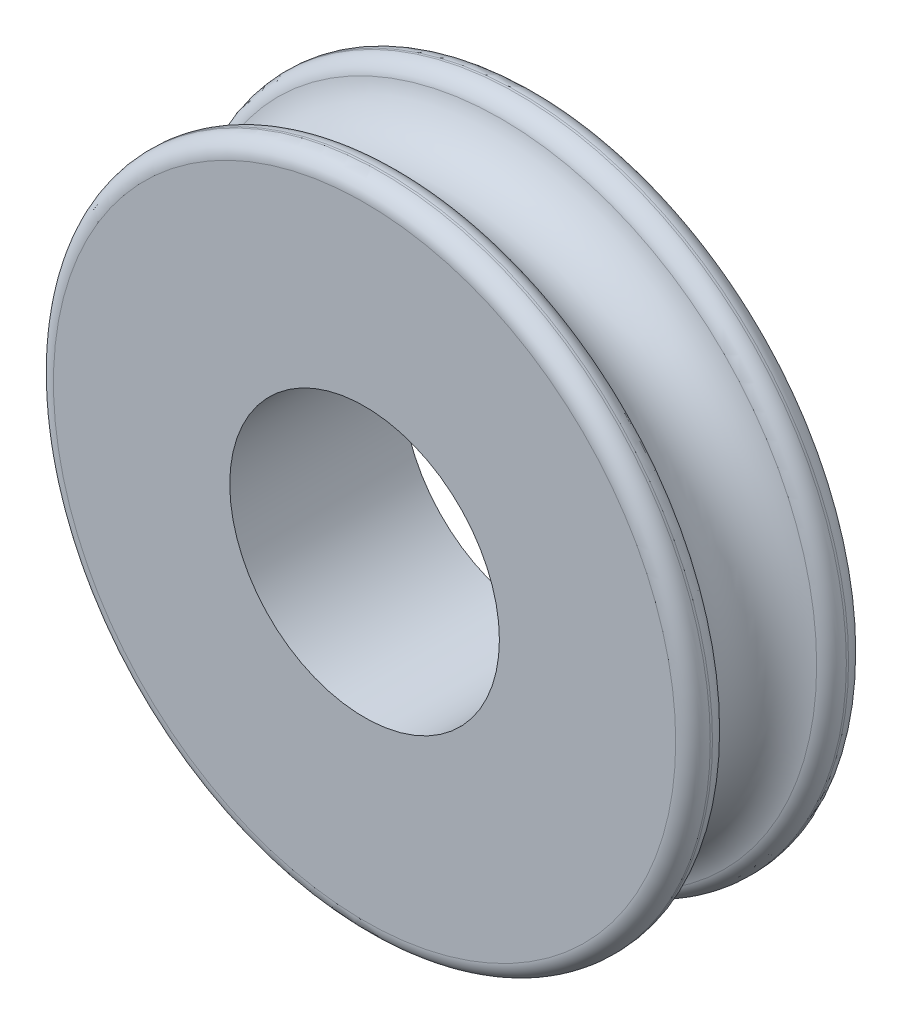
SolidWorks part; units mm, degrees
ref_plane "Front Plane" through (0, 0, 0) normal (0, 0, 1) x (1, 0, 0)
ref_plane "Top Plane" through (0, 0, 0) normal (0, 1, 0) x (1, 0, 0)
ref_plane "Right Plane" through (0, 0, 0) normal (1, 0, 0) x (0, 0, -1)
sketch "Эскиз1" plane through (0, 0, 0) normal (0, 0, 1) x (1, 0, 0)
  circle A0 centre (0, 0) radius 3.9
  circle A1 centre (0, 0) radius 9.5
  dimension "D1" = 7.8
  dimension "D2" = 19
extrude "Бобышка-Вытянуть1" add sketch "Эскиз1" along normal mid plane 5
sketch "Эскиз3" plane through (0, 0, 0) normal (0, 1, 0) x (1, 0, 0)
  line L0 (-13.6733, 0) -> (12.4977, 0) construction
  line L2 (9.5, -2.5) -> (9.5, 2.5) construction
  circle A0 centre (9.5, 0) radius 1.5
  point P3 (9.5, 0)
  point P5 (9.5, 0)
  dimension "D1" = 3
sketch "Эскиз4" plane through (0, 0, 0) normal (0, 0, 1) x (1, 0, 0)
  circle A0 centre (0, 0) radius 9.5 construction
  circle A1 centre (0, 0) radius 9.5
sweep "Вырез-По траектории1" cut profiles "Эскиз3" path "Эскиз4"
fillet "Скругление1" radius 0.5 2 edges at (9.5, 0, 2.5) (9.5, 0, -2.5)
fillet "Скругление2" radius 0.5 2 edges at (-9.5, 0, 1.5) (9.5, 0, -1.5)
